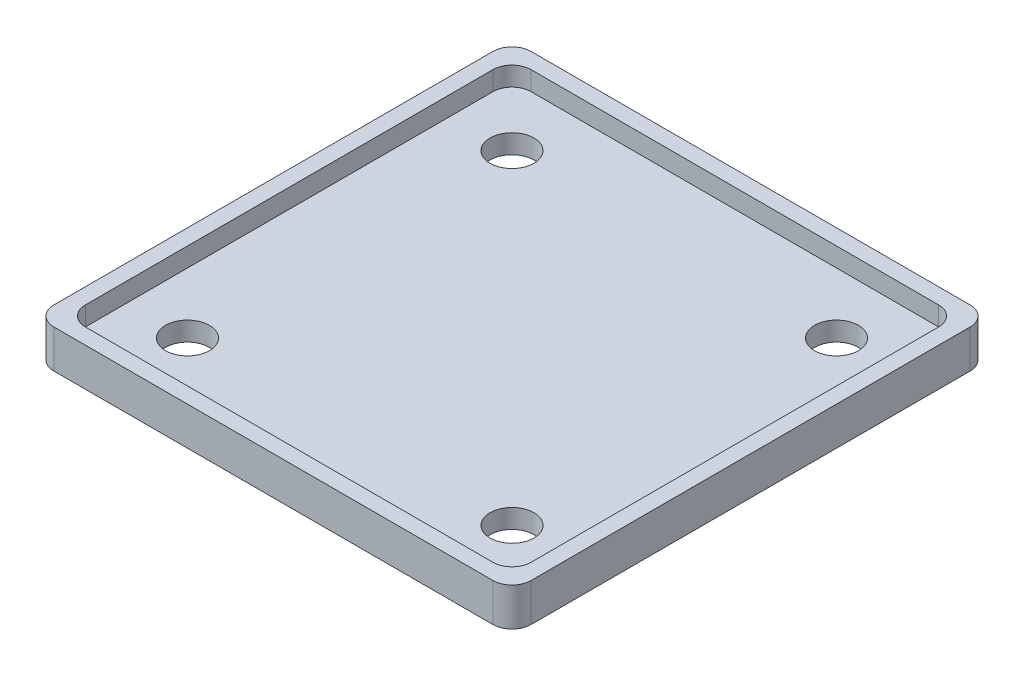
SolidWorks part; units mm, degrees
ref_plane "Front Plane" through (0, 0, 0) normal (0, 0, 1) x (1, 0, 0)
ref_plane "Top Plane" through (0, 0, 0) normal (0, 1, 0) x (1, 0, 0)
ref_plane "Right Plane" through (0, 0, 0) normal (1, 0, 0) x (0, 0, -1)
sketch "Sketch1" plane through (0, 0, 0) normal (0, 1, 0) x (1, 0, 0)
  line L1 (-12.5, -12.5) -> (12.5, -12.5)
  line L2 (-12.5, -12.5) -> (-12.5, 12.5)
  line L3 (-12.5, 12.5) -> (12.5, 12.5)
  line L4 (12.5, -12.5) -> (12.5, 12.5)
  line L5 (-12.5, -12.5) -> (12.5, 12.5) construction
  line L6 (-12.5, 12.5) -> (12.5, -12.5) construction
  point P0 (0, 0)
  dimension "D1" = 25
  dimension "D2" = 25
extrude "Boss-Extrude1" add sketch "Sketch1" along normal blind 2
sketch "Sketch2" plane through (0, 2, 0) normal (0, 1, 0) x (1, 0, 0)
  line L0 (0, 12.5) -> (0, -12.5) construction
  line L1 (12.5, 12.5) -> (-12.5, 12.5) construction
  line L2 (-12.5, -12.5) -> (12.5, -12.5) construction
  line L3 (-12.5, 0) -> (12.5, 0) construction
  line L4 (-12.5, 12.5) -> (-12.5, -12.5) construction
  line L5 (12.5, -12.5) -> (12.5, 12.5) construction
  circle A0 centre (-8.5, 8.5) radius 1.15
  circle A1 centre (-8.5, -8.5) radius 1.15
  circle A2 centre (8.5, -8.5) radius 1.15
  circle A3 centre (8.5, 8.5) radius 1.15
  point P16 (-7.715, 5.3163)
  dimension "D1" = 2.3
  dimension "D2" = 17
  dimension "D3" = 17
extrude "Cut-Extrude1" cut sketch "Sketch2" against normal blind 2
sketch "Sketch3" plane through (0, 2, 0) normal (0, 1, 0) x (1, 0, 0)
  line L1 (10.675, -11.675) -> (-10.675, -11.675)
  line L2 (11.675, -10.675) -> (11.675, 10.675)
  line L3 (10.675, 11.675) -> (-10.675, 11.675)
  line L4 (-11.675, -10.675) -> (-11.675, 10.675)
  line L5 (11.675, -11.675) -> (-11.675, 11.675) construction
  line L6 (11.675, 11.675) -> (-11.675, -11.675) construction
  arc A0 (10.675, -11.675) -> (11.675, -10.675) centre (10.675, -10.675) ccw
  arc A1 (-10.675, -11.675) -> (-11.675, -10.675) centre (-10.675, -10.675) cw
  arc A2 (-10.675, 11.675) -> (-11.675, 10.675) centre (-10.675, 10.675) ccw
  arc A3 (11.675, 10.675) -> (10.675, 11.675) centre (10.675, 10.675) ccw
  point P0 (0, 0)
  dimension "D3" = 1
  dimension "D1" = 23.35
  dimension "D2" = 23.35
extrude "Cut-Extrude2" cut sketch "Sketch3" against normal blind 1
fillet "Fillet1" radius 1 4 edges at (-12.5, 1, -12.5) (-12.5, 1, 12.5) (12.5, 1, -12.5) (12.5, 1, 12.5)
